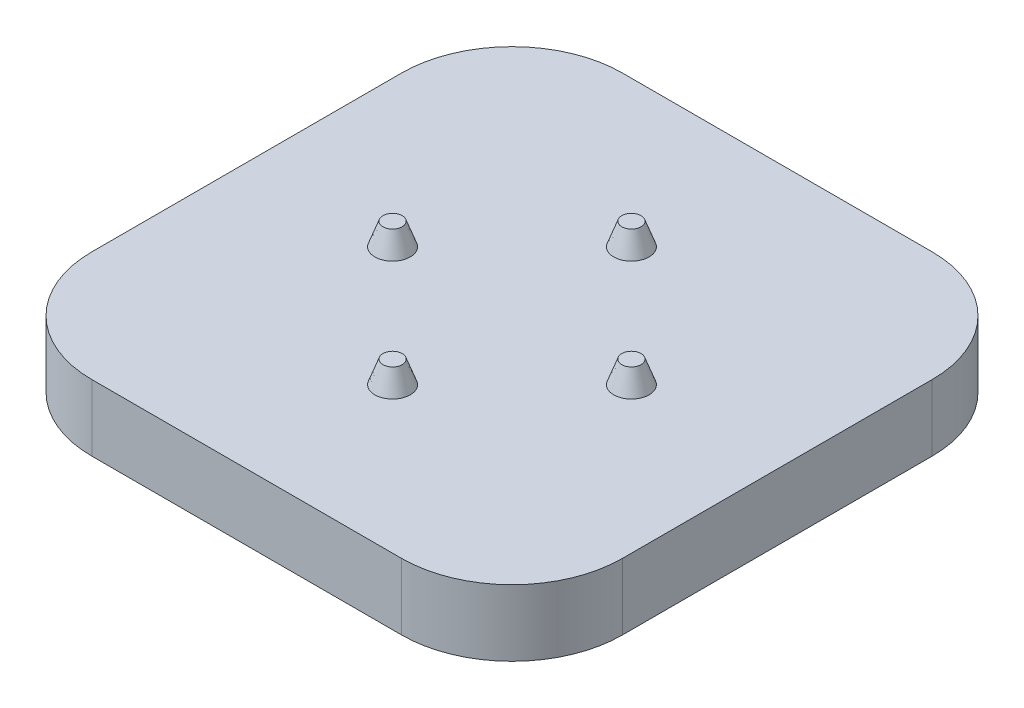
SolidWorks part; units mm, degrees
ref_plane "Alzado" through (0, 0, 0) normal (0, 0, 1) x (1, 0, 0)
ref_plane "Planta" through (0, 0, 0) normal (0, 1, 0) x (1, 0, 0)
ref_plane "Vista lateral" through (0, 0, 0) normal (1, 0, 0) x (0, 0, -1)
sketch "Croquis2" plane through (0, 0, 0) normal (0, 1, 0) x (1, 0, 0)
  line L1 (6, 6) -> (-6, 6)
  line L2 (6, 6) -> (6, -6)
  line L3 (6, -6) -> (-6, -6)
  line L4 (-6, 6) -> (-6, -6)
  line L5 (6, 6) -> (-6, -6) construction
  line L6 (6, -6) -> (-6, 6) construction
  point P0 (0, 0)
  dimension "D1" = 12
  dimension "D2" = 12
extrude "Plataforma" add sketch "Croquis2" along normal blind 1.5
fillet "Redondeo3" radius 2.5 4 edges at (-6, 0.75, 6) (-6, 0.75, -6) (6, 0.75, -6) (6, 0.75, 6)
sketch "Base" plane through (0, 1.5, 0) normal (0, 1, 0) x (1, 0, 0)
  line L1 (3.25, 3.25) -> (-3.25, 3.25)
  line L2 (3.25, 3.25) -> (3.25, -3.25)
  line L3 (3.25, -3.25) -> (-3.25, -3.25)
  line L4 (-3.25, 3.25) -> (-3.25, -3.25)
  line L5 (3.25, 3.25) -> (-3.25, -3.25) construction
  line L6 (3.25, -3.25) -> (-3.25, 3.25) construction
  circle A0 centre (-2.7, 0) radius 0.4
  circle A1 centre (0, 2.7) radius 0.4
  circle A2 centre (0, -2.7) radius 0.4
  circle A3 centre (2.7, 0) radius 0.4
  point P0 (0, 0)
  dimension "D3" = 0.55
  dimension "D1" = 6.5
  dimension "D2" = 6.5
  dimension "D4" = 0.55
  dimension "D5" = 0.55
  dimension "D6" = 0.55
sketch "Croquis16" plane through (0, 1.5, 0) normal (0, 1, 0) x (1, 0, 0)
  circle A0 centre (-2.7, 0) radius 0.4
  circle A1 centre (0, -2.7) radius 0.4
  circle A2 centre (2.7, 0) radius 0.4
  circle A3 centre (0, 2.7) radius 0.4
extrude "Saliente-Extruir7" add sketch "Croquis16" along normal blind 0.5 draft 20
scale "Escala1" scale about centroid uniform scaling yes scale factor 10
